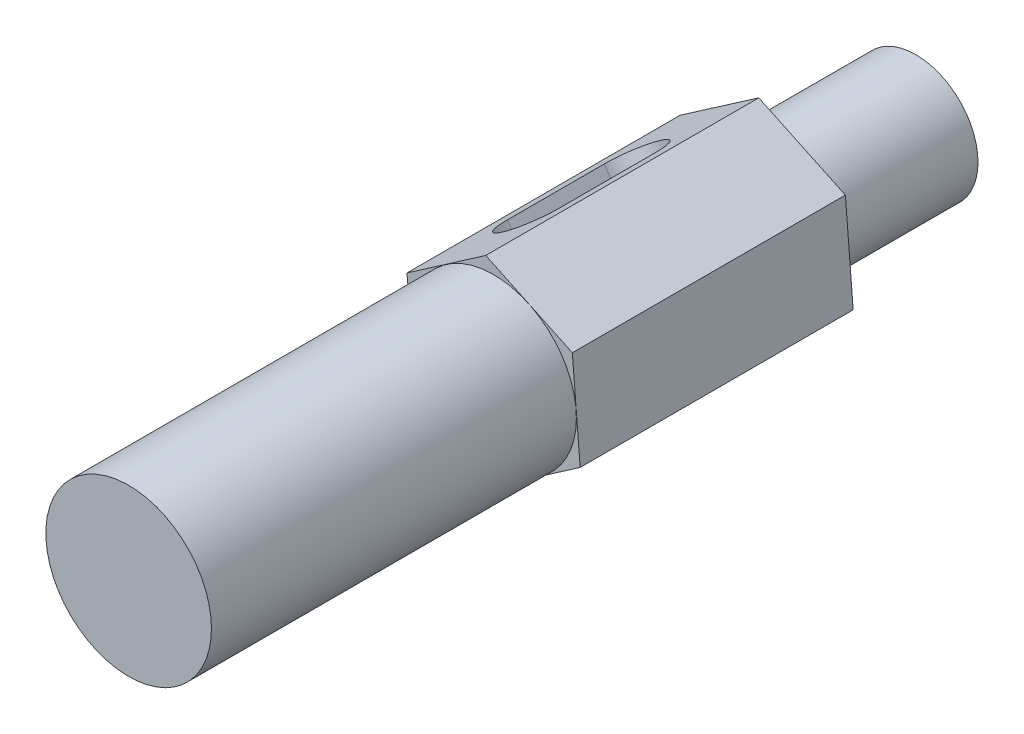
SolidWorks part; units mm, degrees
ref_plane "Front Plane" through (0, 0, 0) normal (0, 0, 1) x (1, 0, 0)
ref_plane "Top Plane" through (0, 0, 0) normal (0, 1, 0) x (1, 0, 0)
ref_plane "Right Plane" through (0, 0, 0) normal (1, 0, 0) x (0, 0, -1)
sketch "Sketch1" plane through (0, 0, 0) normal (0, 0, 1) x (1, 0, 0)
  line L1 (6.0296, 4.1722) -> (-0.5985, 7.3079)
  line L2 (-0.5985, 7.3079) -> (-6.6281, 3.1356)
  line L3 (-6.6281, 3.1356) -> (-6.0296, -4.1722)
  line L4 (-6.0296, -4.1722) -> (0.5985, -7.3079)
  line L5 (0.5985, -7.3079) -> (6.6281, -3.1356)
  line L6 (6.6281, -3.1356) -> (6.0296, 4.1722)
  circle A0 centre (0, 0) radius 6.35 construction
  circle A1 centre (0, 0) radius 2.7305
  dimension "D2" = 5.461
  dimension "D1" = 12.7
extrude "Boss-Extrude1" add sketch "Sketch1" along normal blind 20.9042
sketch "Sketch2" plane through (0, 0, 20.9042) normal (0, 0, 1) x (1, 0, 0)
  circle A0 centre (0, 0) radius 6.3398
  dimension "D1" = 12.6797
extrude "Boss-Extrude2" add sketch "Sketch2" along normal blind 27.94
sketch "Sketch3" plane through (0, 0, 0) normal (0, 0, -1) x (-1, 0, 0)
  circle A0 centre (0, 0) radius 4.7536
  circle A1 centre (0, 0) radius 2.7305
  dimension "D1" = 9.5072
  dimension "D2" = 5.461
extrude "Boss-Extrude3" add sketch "Sketch3" along normal blind 11.43
sketch "Sketch4" plane through (-3.6133, 5.2218, 0) normal (-0.569, 0.8223, 0) x (0.8223, 0.569, 0)
  line L0 (0, -14.2748) -> (0, -6.858) construction
  line L1 (-2.3876, -14.2748) -> (-2.3876, -6.858)
  line L2 (2.3876, -14.2748) -> (2.3876, -6.858)
  line L3 (3.6662, -20.9042) -> (-3.6662, -20.9042) construction
  line L4 (3.6662, 0) -> (-3.6662, 0) construction
  arc A0 (-2.3876, -14.2748) -> (2.3876, -14.2748) centre (0, -14.2748) ccw
  arc A1 (2.3876, -6.858) -> (-2.3876, -6.858) centre (0, -6.858) ccw
  point P3 (0, -10.5664)
  dimension "D1" = 2.3876
  dimension "D2" = 6.6294
  dimension "D3" = 6.858
extrude "Cut-Extrude1" cut sketch "Sketch4" against normal up to surface (12.7 mm away) up to face at (3.6133, -5.2218, 10.4521)
